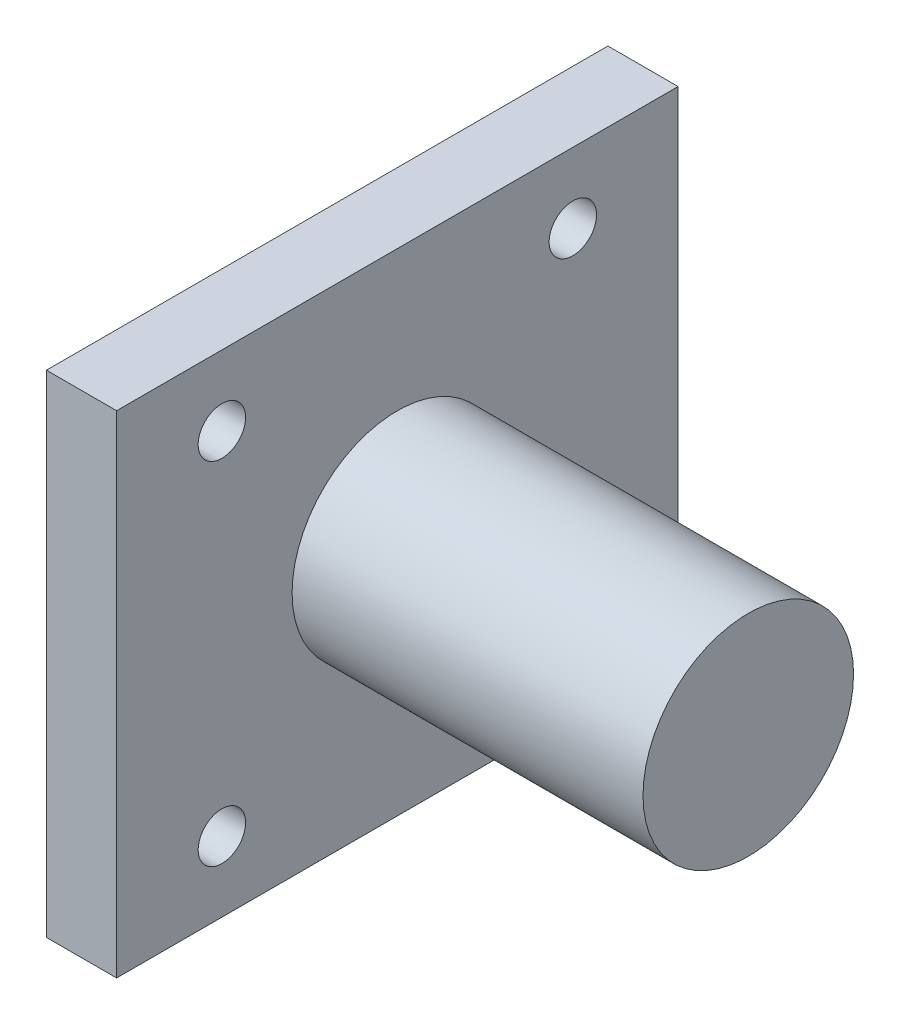
SolidWorks part; units mm, degrees
material "AISI 304"
ref_plane "Front Plane" through (0, 0, 0) normal (0, 0, 1) x (1, 0, 0)
ref_plane "Top Plane" through (0, 0, 0) normal (0, 1, 0) x (1, 0, 0)
ref_plane "Right Plane" through (0, 0, 0) normal (1, 0, 0) x (0, 0, -1)
sketch "Sketch1" plane through (0, 0, 0) normal (1, 0, 0) x (0, 0, -1)
  line L1 (-40, 35) -> (40, 35)
  line L2 (-40, 35) -> (-40, -35)
  line L3 (-40, -35) -> (40, -35)
  line L4 (40, 35) -> (40, -35)
  line L5 (-40, 35) -> (40, -35) construction
  line L6 (-40, -35) -> (40, 35) construction
  point P0 (0, 0)
  dimension "D1" = 80
  dimension "D2" = 70
extrude "Boss-Extrude1" add sketch "Sketch1" along normal blind 10
sketch "Sketch2" plane through (10, 0, 0) normal (1, 0, 0) x (0, 0, -1)
  circle A0 centre (0, 0) radius 15
  dimension "D1" = 30
extrude "Boss-Extrude2" add sketch "Sketch2" along normal blind 50 and the other way blind 25
hole_wizard "1/4 Clearance Hole1" positions "Sketch3" profile "Sketch4" hole size "1/4" standard "ANSI Inch"
sketch "Sketch3" plane through (10, 0, 0) normal (1, 0, 0) x (0, 0, -1)
  point P0 (-25, 25)
  dimension "D1" = 25
  dimension "D2" = 25
sketch "Sketch4" plane through (10, 25, 25) normal (0, 1, 0) x (0, 0, -1)
  line L0 (0, 0) -> (0, 31.2398)
  line L1 (0, 31.2398) -> (3.3782, 29.21)
  line L2 (3.3782, 29.21) -> (3.3782, 0)
  line L5 (3.3782, 0) -> (0, 0)
  line L10 (0, 31.2398) -> (-3.3782, 29.21) construction
  line L11 (0, -6.35) -> (0, 107.95) construction
  dimension "Hole Dia." = 6.7564
  dimension "Hole Depth" = 29.21
  dimension "Drill Angle" = 118
pattern_linear "LPattern1" count 2 spacing 50 along (0, 0, -1) count 2 spacing 50 along (0, -1, 0) of "1/4 Clearance Hole1"
